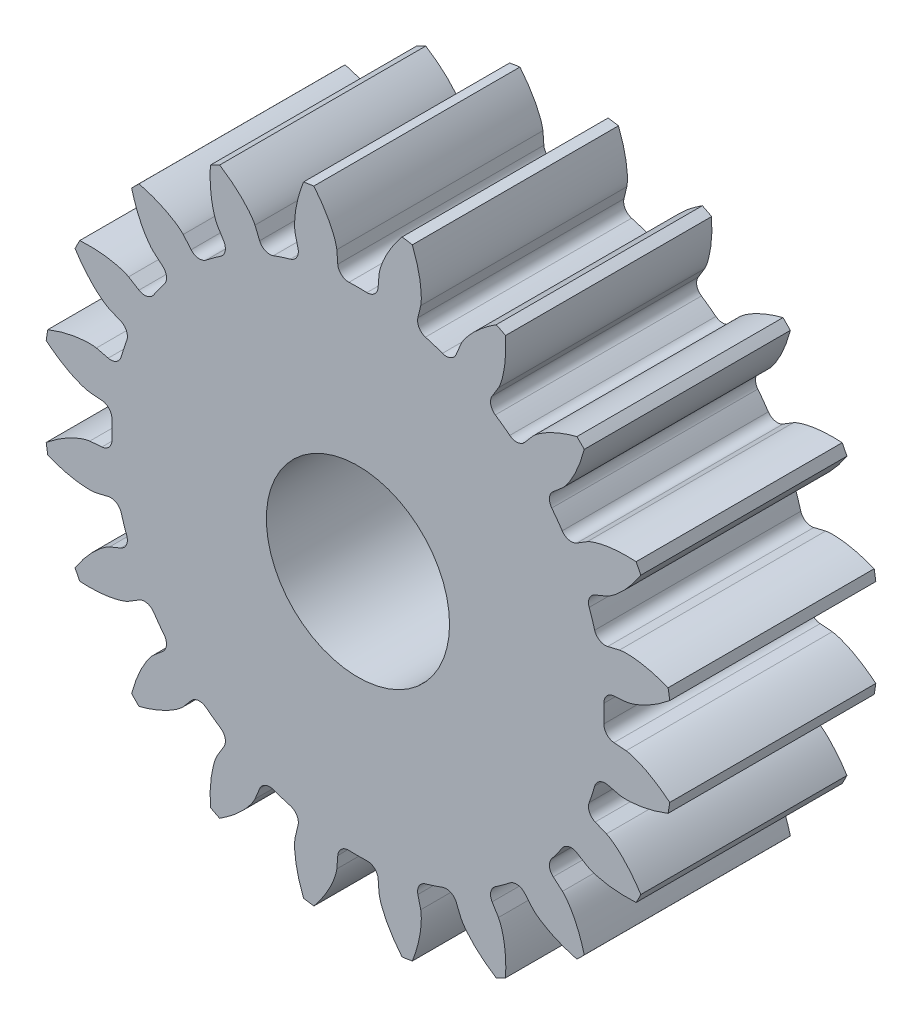
SolidWorks part; units mm, degrees
ref_plane "Front Plane" through (0, 0, 0) normal (0, 0, 1) x (1, 0, 0)
ref_plane "Top Plane" through (0, 0, 0) normal (0, 1, 0) x (1, 0, 0)
ref_plane "Right Plane" through (0, 0, 0) normal (1, 0, 0) x (0, 0, -1)
ref_axis "Gear Axis" through (0, 0, -0.4501) along (0, 0, 1)
sketch "Blank Sketch" plane through (0, 0, 0) normal (0, 0, 1) x (1, 0, 0)
  circle A0 centre (0, 0) radius 13.75
  dimension "OD" = 27.5
extrude "Blank" add sketch "Blank Sketch" along normal blind 9
sketch "Tooth Space Sketch" plane through (0, 0, 0) normal (0, 0, 1) x (1, 0, 0)
  line L0 (11.7099, 0.9227) -> (11.1803, 0.881)
  line L1 (11.7099, -0.9227) -> (11.1803, -0.881)
  line L2 (14.6961, 3.0042) -> (14.6961, -3.0042)
  arc A0 (11.1803, 0.881) -> (10.7429, 0.3902) centre (11.2176, 0.4075) ccw
  arc A1 (10.7429, -0.3902) -> (11.1803, -0.881) centre (11.2176, -0.4075) ccw
  arc A2 (10.7429, -0.3902) -> (10.7429, 0.3902) centre (0, 0) ccw
  spline S0 degree 4 poles (11.7099, 0.9227) (11.7153, 0.9232) (11.7306, 0.925) (11.7593, 0.9294) (11.806, 0.9382) (11.8651, 0.9517) (11.9409, 0.9719) (12.0295, 0.999) (12.1261, 1.0323) (12.2301, 1.0723) (12.3329, 1.1155) (12.4344, 1.1617) (12.5347, 1.2105) (12.6549, 1.2727) (12.7975, 1.3519) (12.9615, 1.4507) (13.1443, 1.5703) (13.3269, 1.7) (13.5034, 1.834) (13.678, 1.9766) (13.8441, 2.1196) (14.0125, 2.2754) (14.1658, 2.4228) (14.3326, 2.5956) (14.4659, 2.7374) (14.6362, 2.9324) (14.7351, 3.0499) (14.8489, 3.1902) (14.8984, 3.2539) (14.9289, 3.293) knots 0 0 0 0 0 0.005377 0.015084 0.028532 0.04661 0.064855 0.092111 0.119476 0.146842 0.174209 0.201575 0.228941 0.256307 0.307035 0.361767 0.4165 0.471232 0.525964 0.580697 0.635429 0.690161 0.744894 0.799626 0.854358 0.909091 0.954545 1 1 1 1 1 construction
  spline S1 degree 4 poles (11.7099, 0.9227) (11.7153, 0.9232) (11.7306, 0.925) (11.7593, 0.9294) (11.806, 0.9382) (11.8651, 0.9517) (11.9409, 0.9719) (12.0295, 0.999) (12.1261, 1.0323) (12.2301, 1.0723) (12.3329, 1.1155) (12.4344, 1.1617) (12.5347, 1.2105) (12.6549, 1.2727) (12.7975, 1.3519) (12.9615, 1.4507) (13.1443, 1.5703) (13.3269, 1.7) (13.5034, 1.834) (13.678, 1.9766) (13.8441, 2.1196) (14.0125, 2.2754) (14.1658, 2.4228) (14.3326, 2.5956) (14.4659, 2.7374) (14.5992, 2.8901) (14.6635, 2.9654) (14.6961, 3.0042) knots 0 0 0 0 0 0.005377 0.015084 0.028532 0.04661 0.064855 0.092111 0.119476 0.146842 0.174209 0.201575 0.228941 0.256307 0.307035 0.361767 0.4165 0.471232 0.525964 0.580697 0.635429 0.690161 0.744894 0.799626 0.854358 0.909091 0.909091 0.909091 0.909091 0.909091
  spline S2 degree 4 poles (11.7099, -0.9227) (11.7153, -0.9232) (11.7306, -0.925) (11.7593, -0.9294) (11.806, -0.9382) (11.8651, -0.9517) (11.9409, -0.9719) (12.0295, -0.999) (12.1261, -1.0323) (12.2301, -1.0723) (12.3329, -1.1155) (12.4344, -1.1617) (12.5347, -1.2105) (12.6549, -1.2727) (12.7975, -1.3519) (12.9615, -1.4507) (13.1443, -1.5703) (13.3269, -1.7) (13.5034, -1.834) (13.678, -1.9766) (13.8441, -2.1196) (14.0125, -2.2754) (14.1658, -2.4228) (14.3326, -2.5956) (14.4659, -2.7374) (14.6362, -2.9324) (14.7351, -3.0499) (14.8489, -3.1902) (14.8984, -3.2539) (14.9289, -3.293) knots 0 0 0 0 0 0.005377 0.015084 0.028532 0.04661 0.064855 0.092111 0.119476 0.146842 0.174209 0.201575 0.228941 0.256307 0.307035 0.361767 0.4165 0.471232 0.525964 0.580697 0.635429 0.690161 0.744894 0.799626 0.854358 0.909091 0.954545 1 1 1 1 1 construction
  spline S3 degree 4 poles (11.7099, -0.9227) (11.7153, -0.9232) (11.7306, -0.925) (11.7593, -0.9294) (11.806, -0.9382) (11.8651, -0.9517) (11.9409, -0.9719) (12.0295, -0.999) (12.1261, -1.0323) (12.2301, -1.0723) (12.3329, -1.1155) (12.4344, -1.1617) (12.5347, -1.2105) (12.6549, -1.2727) (12.7975, -1.3519) (12.9615, -1.4507) (13.1443, -1.5703) (13.3269, -1.7) (13.5034, -1.834) (13.678, -1.9766) (13.8441, -2.1196) (14.0125, -2.2754) (14.1658, -2.4228) (14.3326, -2.5956) (14.4659, -2.7374) (14.5992, -2.8901) (14.6635, -2.9654) (14.6961, -3.0042) knots 0 0 0 0 0 0.005377 0.015084 0.028532 0.04661 0.064855 0.092111 0.119476 0.146842 0.174209 0.201575 0.228941 0.256307 0.307035 0.361767 0.4165 0.471232 0.525964 0.580697 0.635429 0.690161 0.744894 0.799626 0.854358 0.909091 0.909091 0.909091 0.909091 0.909091
  dimension "Root" = 10.75
  dimension "Fillet" = 0.475
extrude "Tooth Space" cut sketch "Tooth Space Sketch" against normal through all both and the other way through all both
pattern_circular "Teeth" count 20 over 360 about axis through (0, 0, -0.4501) along (0, 0, 1) of "Tooth Space"
sketch "Bore Sketch" plane through (0, 0, 0) normal (0, 0, 1) x (1, 0, 0)
  circle A0 centre (0, 0) radius 4
  dimension "Bore" = 8
extrude "Bore" cut sketch "Bore Sketch" against normal through all both and the other way through all both
equation "\"No. of Teeth\"= 20"
equation "\"Module\"= 1.25"
equation "\"Bore Diameter\"= 8"
equation "\"Pressure Angle\"= 20"
equation "\"Outer Diameter\"= ( \"No. of Teeth\" + 2 ) * \"Module\""
equation "\"Pitch Diameter\"= \"No. of Teeth\" * \"Module\""
equation "\"Backlash\"= 0.3 * \"Module\""
equation "\"Arc Length\"= ( ( \"Module\" * pi ) / 2 + \"Backlash\" )"
equation "\"Fillet Radius\"= 0.38 * \"Module\""
equation "\"Tooth Depth\"= IIF ( \"Module\" <= 1.25 , \"Module\" * 2.4 , \"Module\" * 2.25 )"
equation "\"Face Width\"= 9"
equation "\"Root Diameter\"= \"Outer Diameter\" - 2 * \"Tooth Depth\""
equation "\"Base Diameter\"= \"Pitch Diameter\" * cos ( \"Pressure Angle\" )"
equation "\"Base Radius\"= \"Base Diameter\" / 2"
equation "\"Tooth Thickness\"= \"Module\" * pi - \"Arc Length\""
equation "\"Half Space Angle\"= ( \"Arc Length\" / \"Pitch Diameter\" ) * 180 / pi"
equation "\"Involute Fn\"= tan ( \"Pressure Angle\" ) - \"Pressure Angle\" * pi / 180"
equation "\"Flank Offset\"= \"Arc Length\" / \"Pitch Diameter\" - \"Involute Fn\""
equation "\"Tip Cap Diameter\"= \"Outer Diameter\" + 2 * \"Module\""
equation "\"Flank Start Diameter\"= IIF ( \"Base Diameter\" >= ( \"Root Diameter\" + 3 * \"Fillet Radius\" ) , \"Base Diameter\" , \"Root Diameter\" + 3 * \"Fillet Radius\" )"
equation "\"Involute t1\"= ( abs ( ( \"Flank Start Diameter\" / \"Base Diameter\" ) ^ 2 - 1 ) ) ^ 0.5"
equation "\"Involute t2\"= ( abs ( ( \"Tip Cap Diameter\" / \"Base Diameter\" ) ^ 2 - 1 ) ) ^ 0.5"
equation "\"Flank Arc Radius\"= ( \"Pitch Diameter\" / 2 ) * sin ( \"Pressure Angle\" )"
equation "\"Flank Centre Angle\"= \"Half Space Angle\" + \"Pressure Angle\""
equation "\"OD@Blank Sketch\"= \"Outer Diameter\""
equation "\"Width@Blank\"= \"Face Width\""
equation "\"Root@Tooth Space Sketch\"= \"Root Diameter\" / 2"
equation "\"Fillet@Tooth Space Sketch\"= \"Fillet Radius\""
equation "\"Count@Teeth\"= \"No. of Teeth\""
equation "\"Bore@Bore Sketch\"= \"Bore Diameter\""
